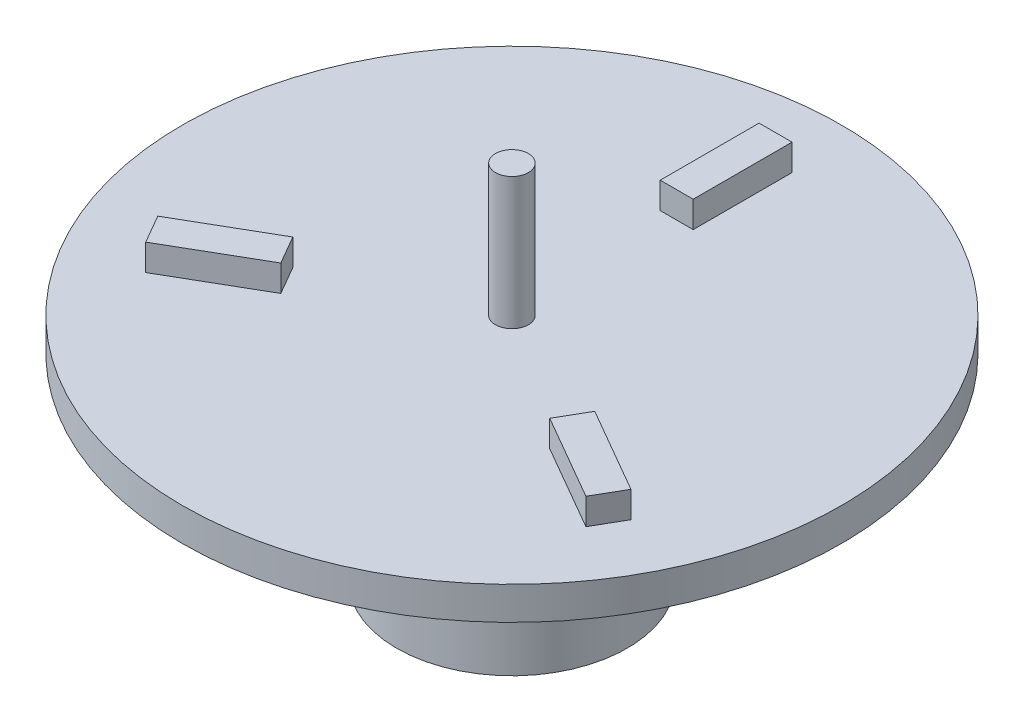
SolidWorks part; units mm, degrees
ref_plane "Plan de face" through (0, 0, 0) normal (0, 0, 1) x (1, 0, 0)
ref_plane "Plan de dessus" through (0, 0, 0) normal (0, 1, 0) x (1, 0, 0)
ref_plane "Plan de droite" through (0, 0, 0) normal (1, 0, 0) x (0, 0, -1)
sketch "Esquisse1" plane through (0, 0, 0) normal (0, 1, 0) x (1, 0, 0)
  circle A0 centre (0, 0) radius 3.5
  dimension "D1" = 7
extrude "Boss.-Extru.1" add sketch "Esquisse1" along normal blind 5
sketch "Esquisse4" plane through (0, 5, 0) normal (0, 1, 0) x (1, 0, 0)
  circle A0 centre (0, 0) radius 5.5
  dimension "D1" = 11
extrude "Boss.-Extru.3" add sketch "Esquisse4" along normal blind 1
sketch "Esquisse5" plane through (0, 6, 0) normal (0, 1, 0) x (1, 0, 0)
  circle A0 centre (0, 0) radius 10
  dimension "D1" = 20
extrude "Boss.-Extru.4" add sketch "Esquisse5" along normal blind 1
sketch "Esquisse6" plane through (0, 7, 0) normal (0, 1, 0) x (1, 0, 0)
  circle A0 centre (0, 0) radius 0.5
  dimension "D1" = 1
extrude "Boss.-Extru.5" add sketch "Esquisse6" along normal blind 4
sketch "Esquisse7" plane through (0, 7, 0) normal (0, 1, 0) x (1, 0, 0)
  line L0 (0, 0) -> (0, 5) construction
  line L1 (0, 5) -> (0.5, 5)
  line L2 (0.5, 5) -> (0.5, 8)
  line L3 (0.5, 8) -> (-0.5, 8)
  line L4 (-0.5, 8) -> (-0.5, 5)
  line L5 (-0.5, 5) -> (0, 5)
  dimension "D1" = 5
  dimension "D2" = 0.5
  dimension "D3" = 0.5
  dimension "D4" = 3
extrude "Boss.-Extru.6" add sketch "Esquisse7" along normal blind 0.8
pattern_circular "Répétition circulaire1" count 3 every 120 about axis through (0, 0, 0) along (0, 1, 0) of "Boss.-Extru.6"
